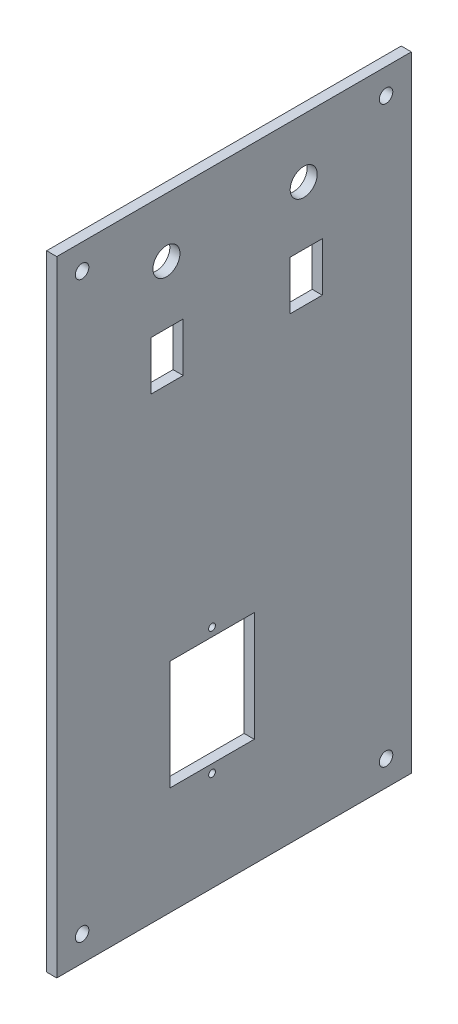
SolidWorks part; units mm, degrees
ref_plane "Front Plane" through (0, 0, 0) normal (0, 0, 1) x (1, 0, 0)
ref_plane "Top Plane" through (0, 0, 0) normal (0, 1, 0) x (1, 0, 0)
ref_plane "Right Plane" through (0, 0, 0) normal (1, 0, 0) x (0, 0, -1)
sketch "Sketch1" plane through (0, 0, 0) normal (1, 0, 0) x (0, 0, -1)
  line L1 (0, 0) -> (210, 0)
  line L2 (0, 0) -> (0, 370)
  line L3 (0, 370) -> (210, 370)
  line L4 (210, 0) -> (210, 370)
  dimension "D1" = 370
  dimension "D2" = 210
extrude "Boss-Extrude1" add sketch "Sketch1" along normal blind 6
sketch "Sketch2" plane through (0, 0, 0) normal (-1, 0, 0) x (0, 0, 1)
  line L1 (-116.9554, 63.9516) -> (-66.9554, 63.9516)
  line L2 (-116.9554, 63.9516) -> (-116.9554, 128.9516)
  line L3 (-116.9554, 128.9516) -> (-66.9554, 128.9516)
  line L4 (-66.9554, 63.9516) -> (-66.9554, 128.9516)
  line L5 (-157.262, 271.5673) -> (-138.262, 271.5673)
  line L6 (-157.262, 271.5673) -> (-157.262, 300.5673)
  line L7 (-157.262, 300.5673) -> (-138.262, 300.5673)
  line L8 (-138.262, 271.5673) -> (-138.262, 300.5673)
  line L9 (-74.8779, 271.5673) -> (-55.8779, 271.5673)
  line L10 (-74.8779, 271.5673) -> (-74.8779, 300.5673)
  line L11 (-74.8779, 300.5673) -> (-55.8779, 300.5673)
  line L12 (-55.8779, 271.5673) -> (-55.8779, 300.5673)
extrude "Cut-Extrude1" cut sketch "Sketch2" against normal blind 10
sketch "Sketch3" plane through (0, 0, 0) normal (-1, 0, 0) x (0, 0, 1)
  circle A0 centre (-91.9554, 133.9516) radius 2
  circle A1 centre (-91.9554, 58.9516) radius 2
extrude "Cut-Extrude2" cut sketch "Sketch3" against normal blind 10
sketch "Sketch4" plane through (6, 0, 0) normal (1, 0, 0) x (0, 0, -1)
  circle A0 centre (146.2416, 335.1604) radius 8
  circle A1 centre (64.9568, 335.1604) radius 8
extrude "Cut-Extrude3" cut sketch "Sketch4" against normal blind 10
sketch "Sketch5" plane through (6, 0, 0) normal (1, 0, 0) x (0, 0, -1)
  circle A0 centre (15, 15.1057) radius 4
  circle A1 centre (15.0001, 355.0529) radius 4
  circle A2 centre (195, 355) radius 4
  circle A3 centre (195, 15.0176) radius 4
  dimension "D1" = 8
  dimension "D2" = 8
  dimension "D3" = 8
  dimension "D4" = 8
extrude "Cut-Extrude4" cut sketch "Sketch5" against normal blind 12
